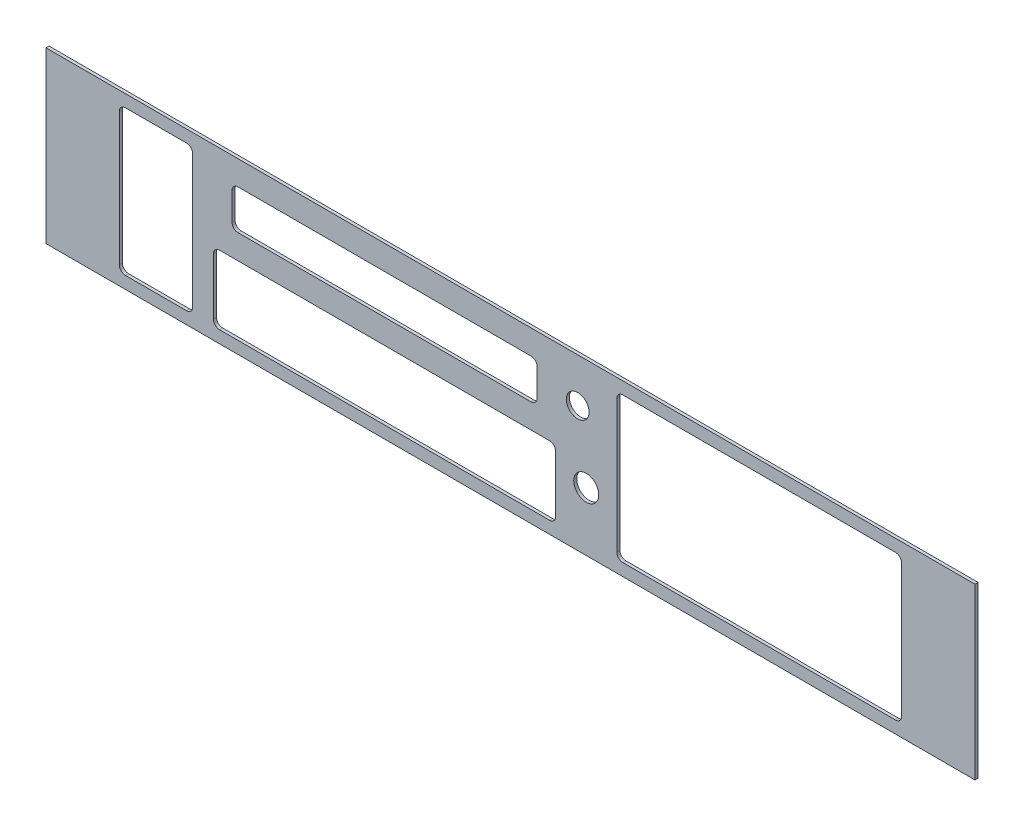
SolidWorks part; units mm, degrees
ref_plane "Front Plane" through (0, 0, 0) normal (0, 0, 1) x (1, 0, 0)
ref_plane "Top Plane" through (0, 0, 0) normal (0, 1, 0) x (1, 0, 0)
ref_plane "Right Plane" through (0, 0, 0) normal (1, 0, 0) x (0, 0, -1)
sketch "Sketch1" plane through (0, 0, 0) normal (0, 0, 1) x (1, 0, 0)
  line L1 (241.3, -44.0499) -> (-241.3, -44.05)
  line L2 (241.3, -44.0499) -> (241.3, 44.05)
  line L3 (241.3, 44.05) -> (-241.3, 44.0499)
  line L4 (-241.3, -44.05) -> (-241.3, 44.0499)
  line L5 (241.3, -44.0499) -> (-241.3, 44.0499) construction
  line L6 (241.3, 44.05) -> (-241.3, -44.05) construction
  point P0 (0, 0)
  dimension "D1" = 88.0999
  dimension "D2" = 482.6
extrude "Boss-Extrude1" add sketch "Sketch1" along normal blind 1.5875
sketch "Sketch2" plane through (0, 0, 1.5875) normal (0, 0, 1) x (1, 0, 0)
  line L0 (241.3, 44.05) -> (-241.3, 44.0499) construction
  line L1 (-144.6606, 31.35) -> (13.8354, 31.35)
  line L2 (-144.6606, 31.35) -> (-144.6606, 10.776)
  line L3 (-144.6606, 10.776) -> (13.8354, 10.776)
  line L4 (13.8354, 31.35) -> (13.8354, 10.776)
  line L5 (-241.3, 44.0499) -> (-241.3, -44.05) construction
  dimension "D1" = 20.574
  dimension "D2" = 158.496
  dimension "D3" = 12.7
  dimension "D4" = 96.6394
extrude "Cut-Extrude1" cut sketch "Sketch2" against normal through all
fillet "Fillet1" radius 3.175 4 edges at (-144.6606, 31.35, 0.7937) (13.8354, 10.776, 0.7937) (13.8354, 31.35, 0.7937) (-144.6606, 10.776, 0.7937)
sketch "Sketch3" plane through (0, 0, 1.5875) normal (0, 0, 1) x (1, 0, 0)
  line L0 (-144.6606, 10.776) -> (13.8354, 10.776) construction
  line L1 (-154.3126, -1.924) -> (23.4874, -1.924)
  line L2 (-154.3126, -1.924) -> (-154.3126, -37.7)
  line L3 (-154.3126, -37.7) -> (23.4874, -37.7)
  line L4 (23.4874, -1.924) -> (23.4874, -37.7)
  line L5 (-241.3, -44.05) -> (241.3, -44.0499) construction
  point P9 (-65.4126, -1.924)
  point P10 (-65.4126, 10.776)
  dimension "D1" = 177.8
  dimension "D2" = 0
  dimension "D3" = 12.7
  dimension "D4" = 6.35
extrude "Cut-Extrude2" cut sketch "Sketch3" against normal through all
fillet "Fillet2" radius 3.175 4 edges at (-154.3126, -37.7, 0.7937) (23.4874, -37.7, 0.7937) (23.4874, -1.924, 0.7937) (-154.3126, -1.924, 0.7937)
sketch "Sketch4" plane through (0, 0, 1.5875) normal (0, 0, 1) x (1, 0, 0)
  line L0 (-241.3, -44.05) -> (241.3, -44.0499) construction
  line L1 (-203.2, 37.7) -> (-165.1, 37.7)
  line L2 (-203.2, 37.7) -> (-203.2, -37.7)
  line L3 (-203.2, -37.7) -> (-165.1, -37.7)
  line L4 (-165.1, 37.7) -> (-165.1, -37.7)
  line L5 (-241.3, 44.0499) -> (-241.3, -44.05) construction
  line L6 (-154.3126, -5.099) -> (-154.3126, -34.525) construction
  line L7 (241.3, 44.05) -> (-241.3, 44.0499) construction
  dimension "D1" = 6.35
  dimension "D2" = 38.1
  dimension "D3" = 10.7874
  dimension "D4" = 6.35
extrude "Cut-Extrude3" cut sketch "Sketch4" against normal through all
sketch "Sketch5" plane through (0, 0, 1.5875) normal (0, 0, 1) x (1, 0, 0)
  line L0 (-241.3, -44.05) -> (241.3, -44.0499) construction
  line L1 (55.2374, 37.7) -> (203.2, 37.7)
  line L2 (55.2374, 37.7) -> (55.2374, -37.7)
  line L3 (55.2374, -37.7) -> (203.2, -37.7)
  line L4 (203.2, 37.7) -> (203.2, -37.7)
  line L5 (23.4874, -34.525) -> (23.4874, -5.099) construction
  line L6 (241.3, 44.05) -> (-241.3, 44.0499) construction
  line L7 (241.3, -44.0499) -> (241.3, 44.05) construction
  dimension "D1" = 6.35
  dimension "D2" = 31.75
  dimension "D3" = 6.35
  dimension "D4" = 38.1
extrude "Cut-Extrude4" cut sketch "Sketch5" against normal blind 1.5875
fillet "Fillet3" radius 3.175 8 edges at (55.2374, 37.7, 0.7937) (203.2, 37.7, 0.7937) (203.2, -37.7, 0.7937) (55.2374, -37.7, 0.7937) (-203.2, -37.7, 0.7937) (-165.1, -37.7, 0.7937) (-165.1, 37.7, 0.7937) (-203.2, 37.7, 0.7937)
sketch "Sketch6" plane through (0, 0, 0) normal (0, 0, -1) x (-1, 0, 0)
  line L0 (-23.4874, -34.525) -> (-23.4874, -5.099) construction
  circle A0 centre (-39.3624, -13.5699) radius 6.5024
  circle A1 centre (-34.9301, 21.1404) radius 5.9207
  dimension "D1" = 15.875
extrude "Cut-Extrude5" cut sketch "Sketch6" against normal through all
